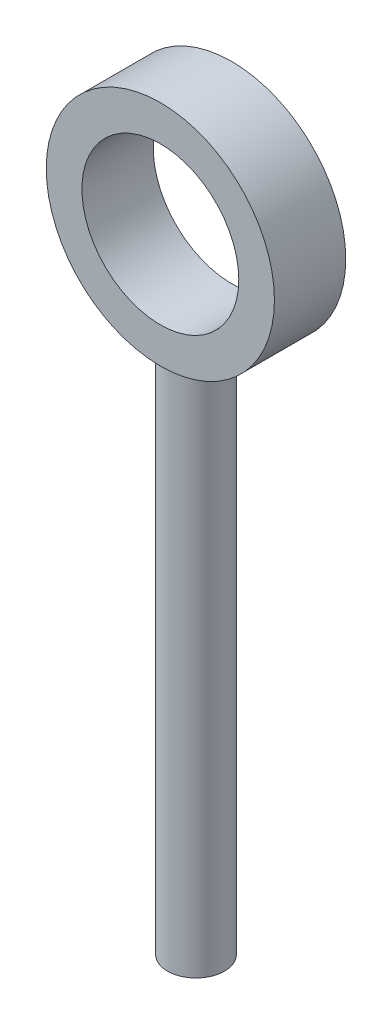
SolidWorks part; units mm, degrees
ref_plane "前视基准面" through (0, 0, 0) normal (0, 0, 1) x (1, 0, 0)
ref_plane "上视基准面" through (0, 0, 0) normal (0, 1, 0) x (1, 0, 0)
ref_plane "右视基准面" through (0, 0, 0) normal (1, 0, 0) x (0, 0, -1)
sketch "草图1" plane through (0, 0, 0) normal (0, 0, 1) x (1, 0, 0)
  circle A0 centre (0, 0) radius 5.5
  circle A1 centre (0, 0) radius 8
  dimension "D1" = 11
  dimension "D2" = 16
extrude "凸台-拉伸1" add sketch "草图1" along normal mid plane 5
ref_plane "基准面1" through (0, -45, 0) normal (0, 1, 0) x (1, 0, 0)
sketch "草图3" plane through (0, -45, 0) normal (0, 1, 0) x (1, 0, 0)
  circle A0 centre (0, 0) radius 2
  dimension "D1" = 4
extrude "凸台-拉伸2" add sketch "草图3" along normal up to surface (37 mm away)
